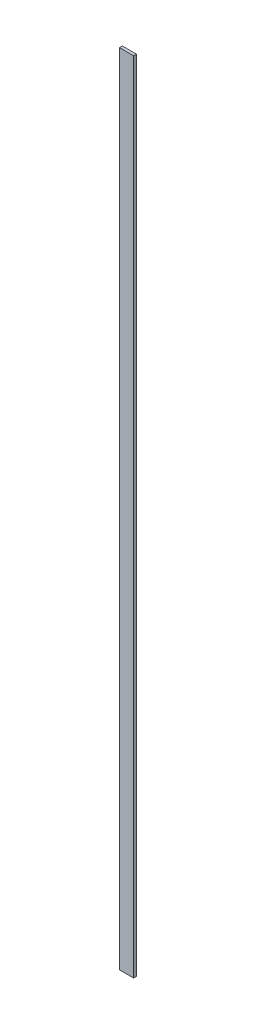
SolidWorks part; units mm, degrees
ref_plane "Front Plane" through (0, 0, 0) normal (0, 0, 1) x (1, 0, 0)
ref_plane "Top Plane" through (0, 0, 0) normal (0, 1, 0) x (1, 0, 0)
ref_plane "Right Plane" through (0, 0, 0) normal (1, 0, 0) x (0, 0, -1)
sketch "Sketch1" plane through (0, 0, 0) normal (0, 1, 0) x (1, 0, 0)
  line L1 (-20, -4) -> (20, -4)
  line L2 (-20, -4) -> (-20, 4)
  line L3 (-20, 4) -> (20, 4)
  line L4 (20, -4) -> (20, 4)
  line L5 (-20, -4) -> (20, 4) construction
  line L6 (-20, 4) -> (20, -4) construction
  point P0 (0, 0)
  dimension "D1" = 40
  dimension "D2" = 8
extrude "Boss-Extrude1" add sketch "Sketch1" along normal mid plane 2280
